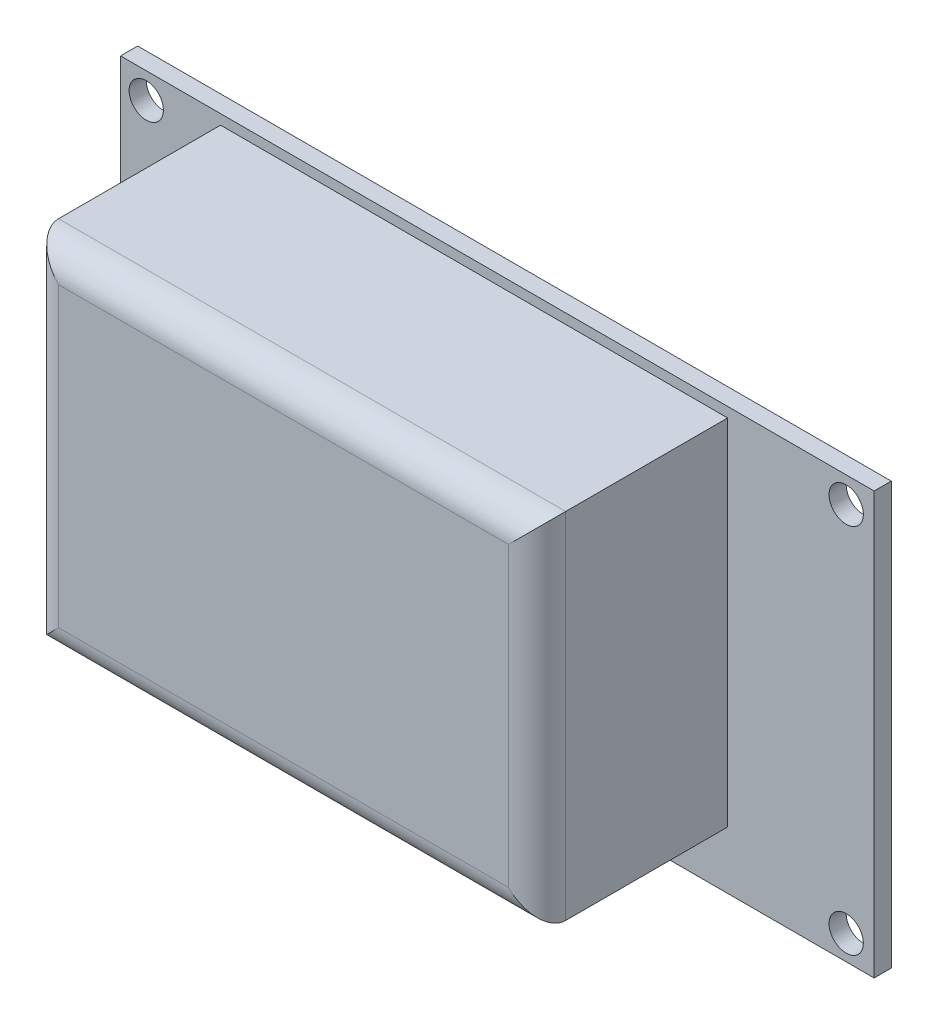
SolidWorks part; units mm, degrees
ref_plane "Front Plane" through (0, 0, 0) normal (0, 0, 1) x (1, 0, 0)
ref_plane "Top Plane" through (0, 0, 0) normal (0, 1, 0) x (1, 0, 0)
ref_plane "Right Plane" through (0, 0, 0) normal (1, 0, 0) x (0, 0, -1)
ref_plane "Plane1" through (0, 0, 0) normal (0, 0, -1) x (-1, 0, 0)
sketch "Sketch1" plane through (0, 0, 0) normal (0, 0, -1) x (-1, 0, 0)
  line L0 (33.5, 18.75) -> (-33.5, 18.75)
  line L1 (-33.5, 18.75) -> (-33.5, -18.75)
  line L2 (-33.5, -18.75) -> (33.5, -18.75)
  line L3 (33.5, -18.75) -> (33.5, 18.75)
extrude "Boss-Extrude1" add sketch "Sketch1" against normal blind 1.524
sketch "Sketch2" plane through (0, 0, 1.524) normal (0, 0, 1) x (1, 0, 0)
  line L0 (20.475, -13.635) -> (-24.61, -13.635)
  line L1 (-24.61, -13.635) -> (-24.61, 17.861)
  line L2 (-24.61, 17.861) -> (20.475, 17.861)
  line L3 (20.475, 17.861) -> (20.475, -13.635)
extrude "Boss-Extrude2" add sketch "Sketch2" along normal blind 16.9418
hole_wizard "Hole1" positions "Sketch4" profile "Sketch3" legacy
sketch "Sketch4" plane through (0, 0, 1.524) normal (0, 0, 1) x (1, 0, 0)
  point P0 (31.016, -16.556)
sketch "Sketch3" plane through (31.016, -16.556, 1.524) normal (1, 0, 0) x (0, -1, 0)
  line L0 (0, 0) -> (0, 1.524)
  line L1 (0, 1.524) -> (1.524, 1.524)
  line L2 (1.524, 1.524) -> (1.524, 0)
  line L3 (1.524, 0) -> (0, 0)
  line L4 (0, 110) -> (0, -10) construction
  dimension "Diameter" = 3.048
  dimension "Depth" = 1.524
hole_wizard "Hole2" positions "Sketch6" profile "Sketch5" legacy
sketch "Sketch6" plane through (0, 0, 0) normal (0, 0, -1) x (-1, 0, 0)
  point P0 (31.214, -16.556)
sketch "Sketch5" plane through (-31.214, -16.556, 0) normal (1, 0, 0) x (0, 1, 0)
  line L0 (0, 0) -> (0, 18.4658)
  line L1 (0, 18.4658) -> (1.524, 18.4658)
  line L2 (1.524, 18.4658) -> (1.524, 0)
  line L3 (1.524, 0) -> (0, 0)
  line L4 (0, 110) -> (0, -10) construction
  dimension "Diameter" = 3.048
  dimension "Depth" = 18.4658
hole_wizard "Hole3" positions "Sketch8" profile "Sketch7" legacy
sketch "Sketch8" plane through (0, 0, 0) normal (0, 0, -1) x (-1, 0, 0)
  point P0 (-31.016, 16.464)
sketch "Sketch7" plane through (31.016, 16.464, 0) normal (1, 0, 0) x (0, 1, 0)
  line L0 (0, 0) -> (0, 18.4658)
  line L1 (0, 18.4658) -> (1.524, 18.4658)
  line L2 (1.524, 18.4658) -> (1.524, 0)
  line L3 (1.524, 0) -> (0, 0)
  line L4 (0, 110) -> (0, -10) construction
  dimension "Diameter" = 3.048
  dimension "Depth" = 18.4658
hole_wizard "Hole4" positions "Sketch10" profile "Sketch9" legacy
sketch "Sketch10" plane through (0, 0, 0) normal (0, 0, -1) x (-1, 0, 0)
  point P0 (31.214, 16.464)
sketch "Sketch9" plane through (-31.214, 16.464, 0) normal (1, 0, 0) x (0, 1, 0)
  line L0 (0, 0) -> (0, 18.4658)
  line L1 (0, 18.4658) -> (1.524, 18.4658)
  line L2 (1.524, 18.4658) -> (1.524, 0)
  line L3 (1.524, 0) -> (0, 0)
  line L4 (0, 110) -> (0, -10) construction
  dimension "Diameter" = 3.048
  dimension "Depth" = 18.4658
fillet "Fillet1" radius 2.54 4 edges at (-24.61, 2.113, 18.4658) (-2.0675, -13.635, 18.4658) (-2.0675, 17.861, 18.4658) (20.475, 2.113, 18.4658)
